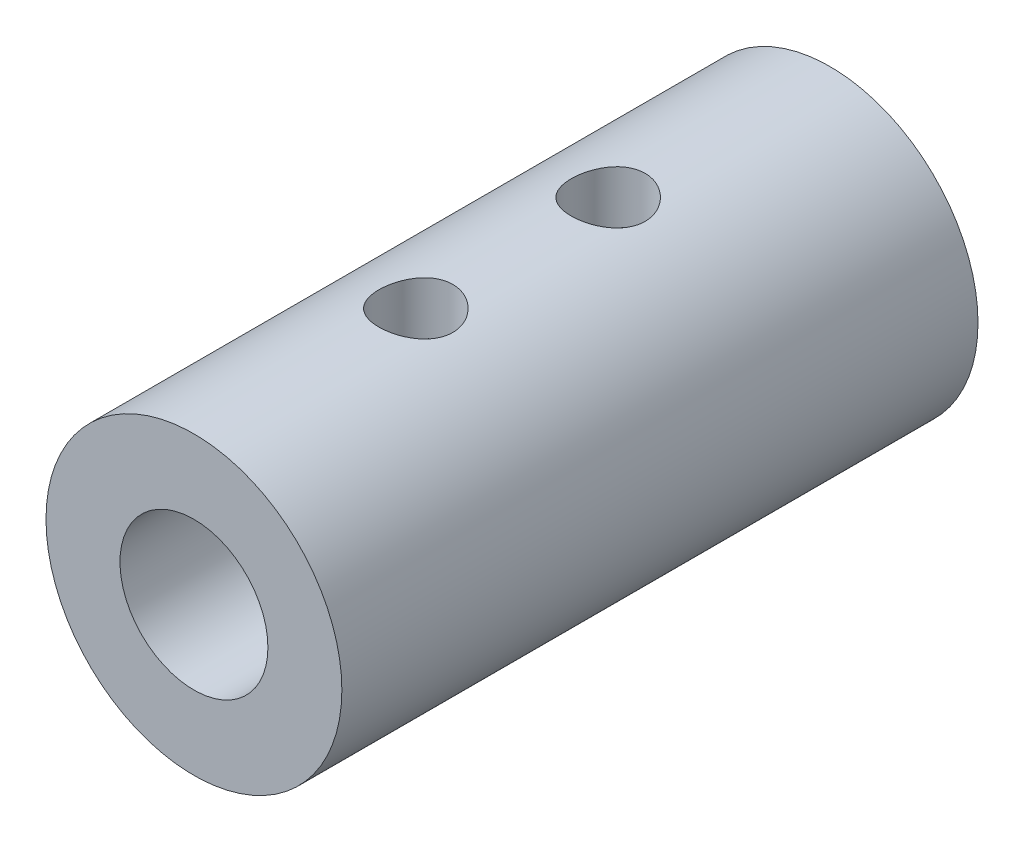
SolidWorks part; units mm, degrees
material "Acero al carbono no aleado"
ref_plane "Alzado" through (0, 0, 0) normal (0, 0, 1) x (1, 0, 0)
ref_plane "Planta" through (0, 0, 0) normal (0, 1, 0) x (1, 0, 0)
ref_plane "Vista lateral" through (0, 0, 0) normal (1, 0, 0) x (0, 0, -1)
sketch "Croquis1" plane through (0, 0, 0) normal (0, 0, 1) x (1, 0, 0)
  circle A5 centre (-9.7363, -4.0832) radius 5
  circle A7 centre (-9.7363, -4.0832) radius 10
  dimension "D2" = 20
  dimension "D13" = 10
extrude "Saliente-Extruir1" add sketch "Croquis1" along normal blind 13
sketch "Croquis2" plane through (0, 0, 0) normal (0, 0, 1) x (1, 0, 0)
  circle A5 centre (-9.7363, -4.0832) radius 6.48
  circle A8 centre (-9.7363, -4.0832) radius 10
  dimension "D13" = 12.96
extrude "Saliente-Extruir2" add sketch "Croquis2" against normal blind 30
sketch "Croquis3" plane through (0, 0, 0) normal (0, 1, 0) x (1, 0, 0)
  line L1 (-3.2563, 30) -> (-16.2163, 30) construction
  line L2 (-19.7363, -13) -> (0.2637, -13) construction
  line L3 (0.2637, -13) -> (0.2637, 30) construction
  circle A0 centre (-9.7363, 15) radius 2.5
  circle A1 centre (-9.7363, 2) radius 2.5
  dimension "D1" = 5
  dimension "D2" = 5
  dimension "D3" = 15
  dimension "D4" = 15
  dimension "D5" = 10
  dimension "D6" = 10
extrude "Cortar-Extruir1" cut sketch "Croquis3" against normal through all both and the other way through all
